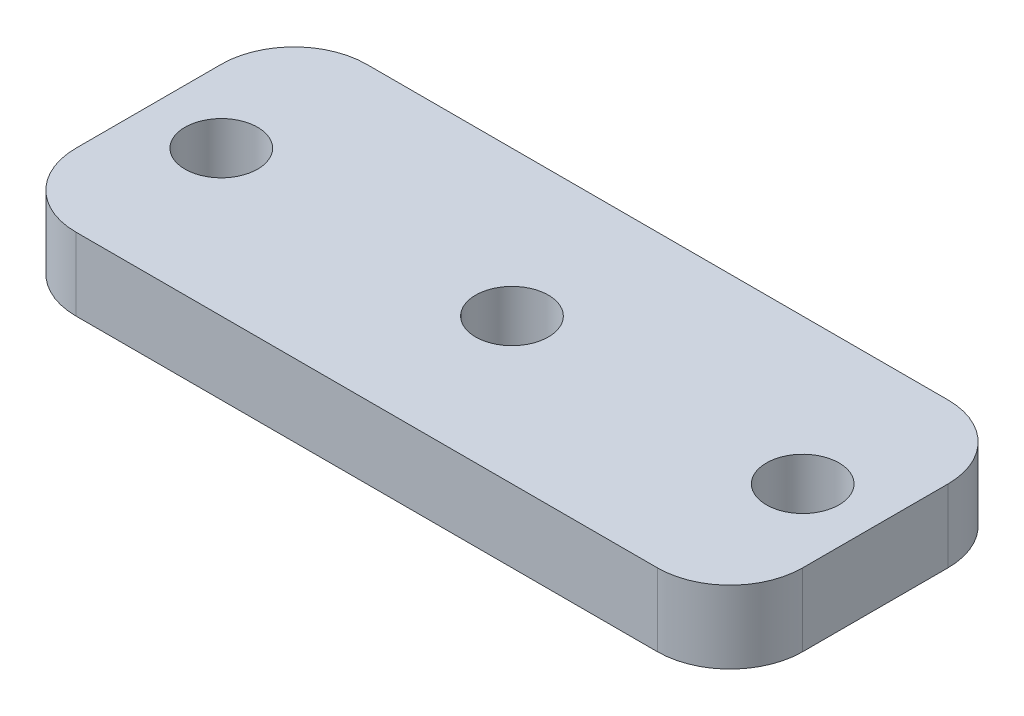
SolidWorks part; units mm, degrees
ref_plane "Front Plane" through (0, 0, 0) normal (0, 0, 1) x (1, 0, 0)
ref_plane "Top Plane" through (0, 0, 0) normal (0, 1, 0) x (1, 0, 0)
ref_plane "Right Plane" through (0, 0, 0) normal (1, 0, 0) x (0, 0, -1)
sketch "Sketch1" plane through (0, 0, 0) normal (0, 1, 0) x (1, 0, 0)
  line L0 (0, 12.7) -> (63.5, 12.7) construction
  line L1 (0, 0) -> (63.5, 0)
  line L2 (0, 0) -> (0, 25.4)
  line L3 (0, 25.4) -> (63.5, 25.4)
  line L4 (63.5, 0) -> (63.5, 25.4)
  line L5 (31.75, 12.7) -> (31.75, 25.4) construction
  circle A0 centre (6.35, 12.7) radius 3.175
  circle A1 centre (31.75, 12.7) radius 3.175
  circle A2 centre (57.15, 12.7) radius 3.175
  dimension "D3" = 6.35
  dimension "D1" = 63.5
  dimension "D2" = 25.4
  dimension "D4" = 25.4
extrude "Boss-Extrude1" add sketch "Sketch1" along normal blind 6.35
fillet "Fillet1" radius 6.35 4 edges at (63.5, 3.175, 0) (63.5, 3.175, -25.4) (0, 3.175, -25.4) (0, 3.175, 0)
